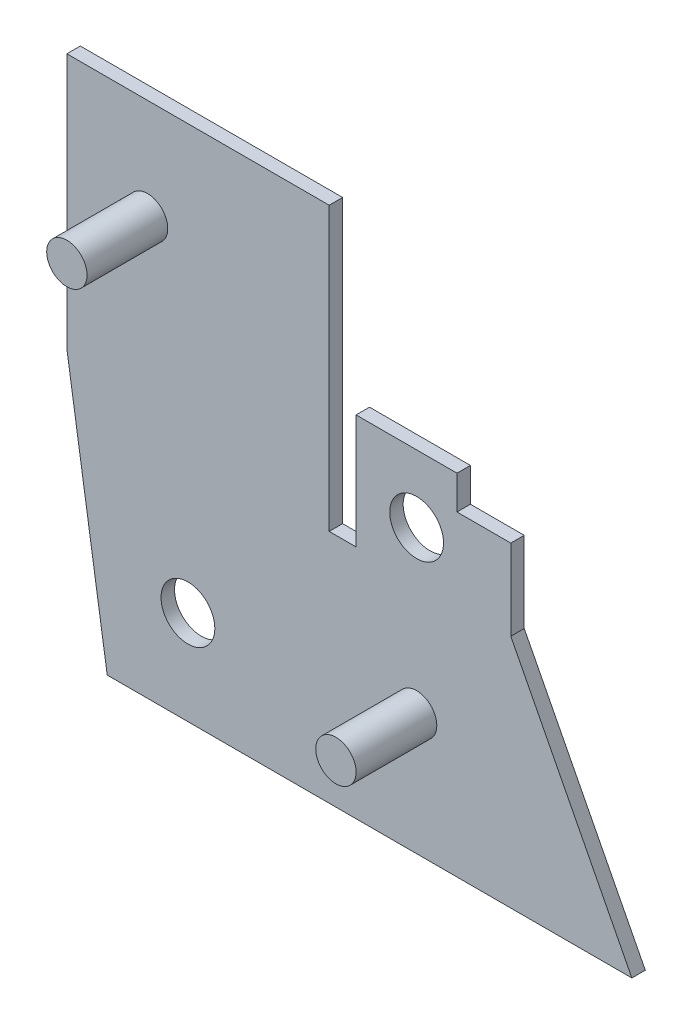
SolidWorks part; units mm, degrees
material "Обычная углеродистая сталь"
ref_plane "Спереди" through (0, 0, 0) normal (0, 0, 1) x (1, 0, 0)
ref_plane "Сверху" through (0, 0, 0) normal (0, 1, 0) x (1, 0, 0)
ref_plane "Справа" through (0, 0, 0) normal (1, 0, 0) x (0, 0, -1)
ref_plane "Плоскость4" through (0, 0, 1) normal (0, 0, 1) x (1, 0, 0)
sketch "Эскиз1" plane through (0, 0, 1) normal (0, 0, 1) x (1, 0, 0)
  line L0 (39, 0) -> (30, 17.5)
  line L1 (30, 17.5) -> (16.5, 17.5)
  line L2 (16.5, 17.5) -> (16.5, 38.5)
  line L3 (16.5, 38.5) -> (-3, 38.5)
  line L4 (-3, 38.5) -> (-3, 19.5)
  line L5 (-3, 19.5) -> (0, 0)
  line L6 (0, 0) -> (39, 0)
extrude "Бобышка-Вытянуть1" add sketch "Эскиз1" against normal blind 1
sketch "Эскиз2" plane through (0, 17.5, 0) normal (0, 1, 0) x (-1, 0, 0)
  line L0 (-30, 1) -> (-18.5, 1)
  line L1 (-18.5, 1) -> (-18.5, 0)
  line L2 (-18.5, 0) -> (-30, 0)
  line L3 (-30, 0) -> (-30, 1)
extrude "Бобышка-Вытянуть2" add sketch "Эскиз2" along normal blind 8.5
sketch "Эскиз3" plane through (0, 0, 0) normal (0, 0, -1) x (-1, 0, 0)
  line L0 (-30, 26) -> (-30, 23.5)
  line L1 (-30, 23.5) -> (-26, 23.5)
  line L2 (-26, 23.5) -> (-26, 26)
  line L3 (-26, 26) -> (-30, 26)
extrude "Вырез-Вытянуть1" cut sketch "Эскиз3" against normal through all
ref_plane "Плоскость5" through (0, 31, 0) normal (0, -1, 0) x (1, 0, 0)
sketch "Эскиз4" plane through (0, 31, 0) normal (0, -1, 0) x (1, 0, 0)
  line L0 (4.5, 7) -> (3, 7)
  line L1 (3, 7) -> (3, 1)
  line L2 (3, 1) -> (4.5, 1)
  line L3 (4.5, 1) -> (4.5, 7)
  line L4 (3, 7) -> (3, 1) construction
revolve "Повернуть1" add sketch "Эскиз4" angle 360 about L4
ref_plane "Плоскость6" through (0, 9, 0) normal (0, -1, 0) x (1, 0, 0)
sketch "Эскиз5" plane through (0, 9, 0) normal (0, -1, 0) x (1, 0, 0)
  line L0 (24.5, 7) -> (23, 7)
  line L1 (23, 7) -> (23, 1)
  line L2 (23, 1) -> (24.5, 1)
  line L3 (24.5, 1) -> (24.5, 7)
  line L4 (23, 7) -> (23, 1) construction
revolve "Повернуть2" add sketch "Эскиз5" angle 360 about L4
hole_wizard "Диаметр отверстия Ø4.0 (4)1" positions "Эскиз7" profile "Эскиз6" hole size "Ø4.0" standard "Ansi Metric"
sketch "Эскиз7" plane through (0, 0, 1) normal (0, 0, 1) x (1, 0, 0)
  point P0 (23, 21)
  point P1 (6, 7)
sketch "Эскиз6" plane through (23, 21, 1) normal (1, 0, 0) x (0, -1, 0)
  line L0 (0, 0) -> (0, 1)
  line L1 (0, 1) -> (2, 1)
  line L2 (2, 1) -> (2, 0)
  line L5 (2, 0) -> (0, 0)
  line L11 (0, -6.35) -> (0, 107.95) construction
  dimension "Диаметр сквозного отверстия" = 4
  dimension "Глубина сквозного отверстия" = 1
